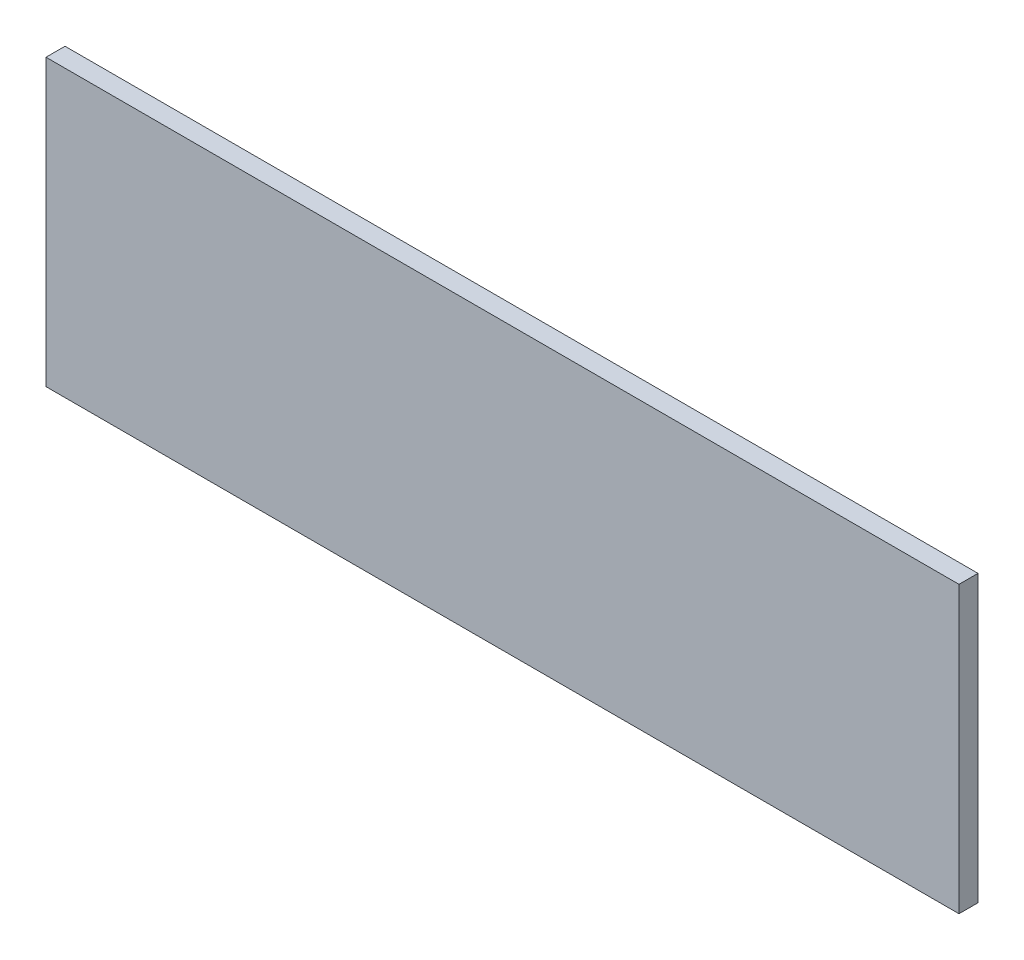
SolidWorks part; units mm, degrees
ref_plane "Front Plane" through (0, 0, 0) normal (0, 0, 1) x (1, 0, 0)
ref_plane "Top Plane" through (0, 0, 0) normal (0, 1, 0) x (1, 0, 0)
ref_plane "Right Plane" through (0, 0, 0) normal (1, 0, 0) x (0, 0, -1)
sketch "Sketch1" plane through (0, 0, 0) normal (0, 0, 1) x (1, 0, 0)
  line L0 (-322.8319, 121.4867) -> (637.1681, 121.4867)
  line L1 (637.1681, 121.4867) -> (637.1681, -178.5133)
  line L2 (637.1681, -178.5133) -> (-322.8319, -178.5133)
  line L3 (-322.8319, -178.5133) -> (-322.8319, 121.4867)
  dimension "D1" = 960
  dimension "D2" = 300
extrude "Boss-Extrude2" add sketch "Sketch1" along normal blind 20 contours L0 L1 L2 L3
